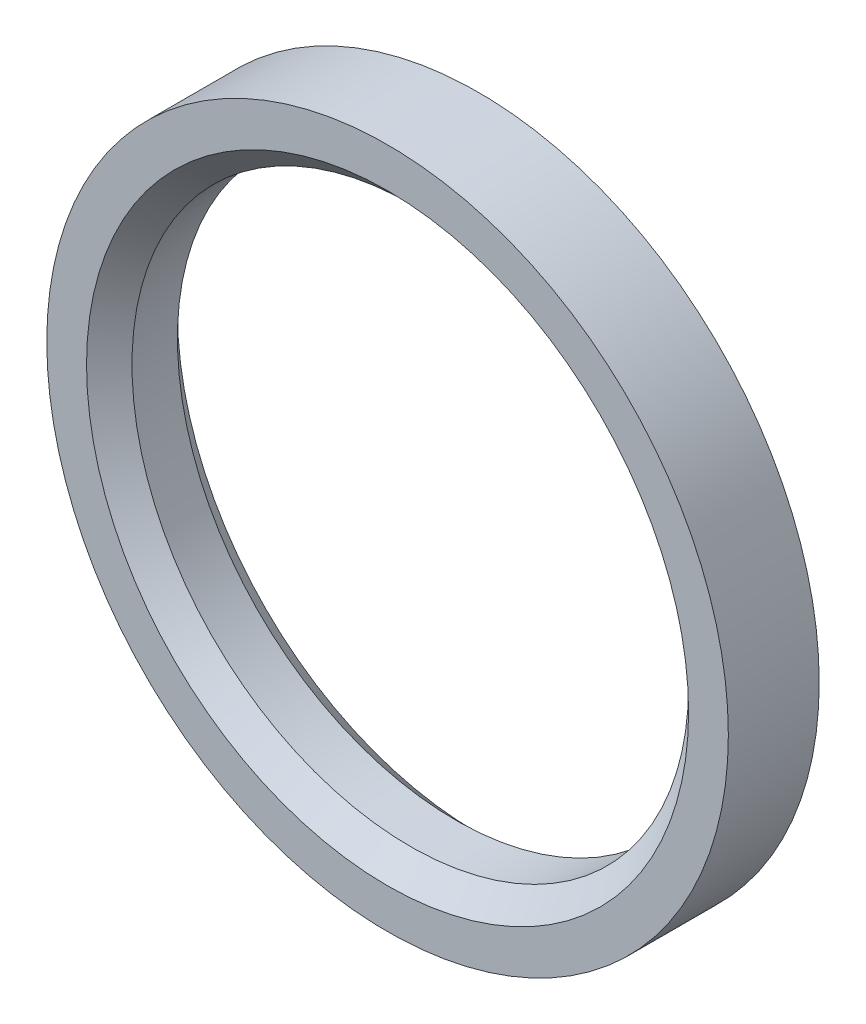
SolidWorks part; units mm, degrees
material "POM 乙缩醛共聚物"
ref_plane "前视基准面" through (0, 0, 0) normal (0, 0, 1) x (1, 0, 0)
ref_plane "上视基准面" through (0, 0, 0) normal (0, 1, 0) x (1, 0, 0)
ref_plane "右视基准面" through (0, 0, 0) normal (1, 0, 0) x (0, 0, -1)
sketch "草图1" plane through (0, 0, 0) normal (0, 0, 1) x (1, 0, 0)
  line L0 (0, 0) -> (0, 100.4243) construction
  circle A0 centre (0, 0) radius 15
  circle A1 centre (0, 0) radius 12.25
  dimension "D1" = 24.5
  dimension "D2" = 30
extrude "凸台-拉伸1" add sketch "草图1" along normal blind 4
chamfer "倒角1" distance 1 angle 45 2 edges at (12.25, 0, 4) (12.25, 0, 0)
equation "\"测试1\"= \"图号代码\""
equation "\"测试2\"= \"名称代码\""
